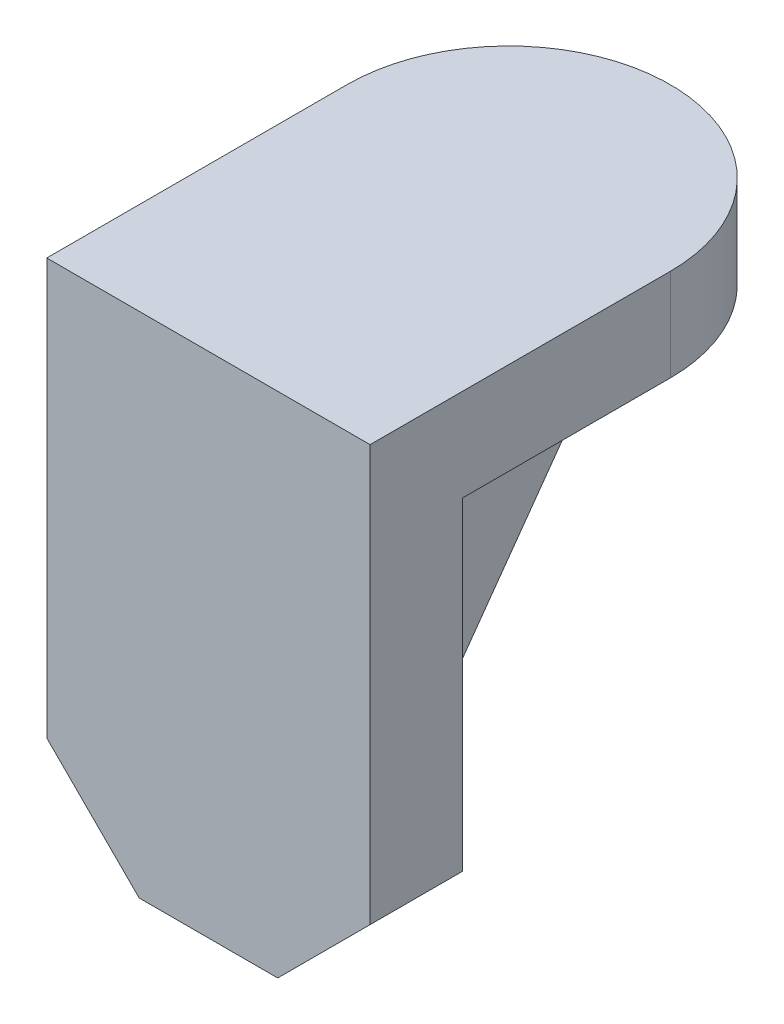
SolidWorks part; units mm, degrees
ref_plane "Front Plane" through (0, 0, 0) normal (0, 0, 1) x (1, 0, 0)
ref_plane "Top Plane" through (0, 0, 0) normal (0, 1, 0) x (1, 0, 0)
ref_plane "Right Plane" through (0, 0, 0) normal (1, 0, 0) x (0, 0, -1)
sketch "Sketch1" plane through (0, 0, 0) normal (0, 0, 1) x (1, 0, 0)
  line L1 (-31.5419, 54.9606) -> (-31.5419, 0.9606)
  line L5 (-31.5419, 0.9606) -> (-19.5419, -11.0394)
  line L6 (-19.5419, -11.0394) -> (-1.5419, -11.0394)
  line L7 (-1.5419, -11.0394) -> (10.4581, 0.9606)
  line L8 (10.4581, 0.9606) -> (10.4581, 54.9606)
  line L9 (-31.5419, 54.9606) -> (10.4581, 54.9606)
  dimension "D1" = 54
  dimension "D2" = 12
  dimension "D3" = 18
  dimension "D4" = 42
  dimension "D5" = 66
  dimension "D6" = 12
  dimension "D7" = 54.9606
  dimension "D8" = 11.1466
extrude "Boss-Extrude2" add sketch "Sketch1" along normal blind 12
sketch "Sketch2" plane through (0, 54.9606, 0) normal (0, 1, 0) x (1, 0, 0)
  line L0 (-31.5419, 0) -> (-31.5419, 27)
  line L1 (10.4581, 0) -> (10.4581, 27)
  line L2 (-31.5419, 0) -> (10.4581, 0)
  line L6 (10.4581, 0) -> (-31.5419, 0)
  line L7 (-31.5419, 0) -> (-31.5419, -12)
  line L8 (-31.5419, -12) -> (10.4581, -12)
  line L9 (10.4581, -12) -> (10.4581, 0)
  line L11 (-31.5419, 0) -> (-31.5419, -12)
  line L13 (10.4581, -12) -> (10.4581, 0)
  line L14 (-31.5419, -12) -> (-31.5419, 0) construction
  line L15 (10.4581, 0) -> (-31.5419, 0) construction
  arc A0 (10.4581, 27) -> (-31.5419, 27) centre (-10.5419, 27) ccw
  line M8 (10.4581, 0) -> (-31.5419, 0)
  dimension "D3" = 0
  dimension "D1" = 27
extrude "Boss-Extrude4" add sketch "Sketch2" against normal blind 12 contours L1 A0 L0 M8
sketch "Sketch5" plane through (0, 42.9606, 0) normal (0, -1, 0) x (1, 0, 0)
  line L0 (10.4581, 0) -> (10.4581, -27) construction
  line L1 (0, -38.7049) -> (-15.3182, -38.7049)
  line L2 (10.4581, 0) -> (-31.5419, 0) construction
  dimension "D1" = 10.4581
  dimension "D2" = 25.7763
  dimension "D3" = 38.7049
ref_plane "Plane2" through (0, -3.7466, -5.2272) normal (0, 0.5826, 0.8128) x (1, 0, 0)
sketch "Sketch7" plane through (0, -3.7466, -5.2272) normal (0, 0.5826, 0.8128) x (1, 0, 0)
  line L0 (-10.5419, -8.9726) -> (-10.5419, 57.5656)
  line L1 (-19.5419, -8.9726) -> (-1.5419, -8.9726) construction
  dimension "D1" = 57.5656
rib "Rib1" sketch "Sketch7" sketch "Sketch7" thickness 12 extrusion direction normal to sketch draft on no parameters "D1"=12
